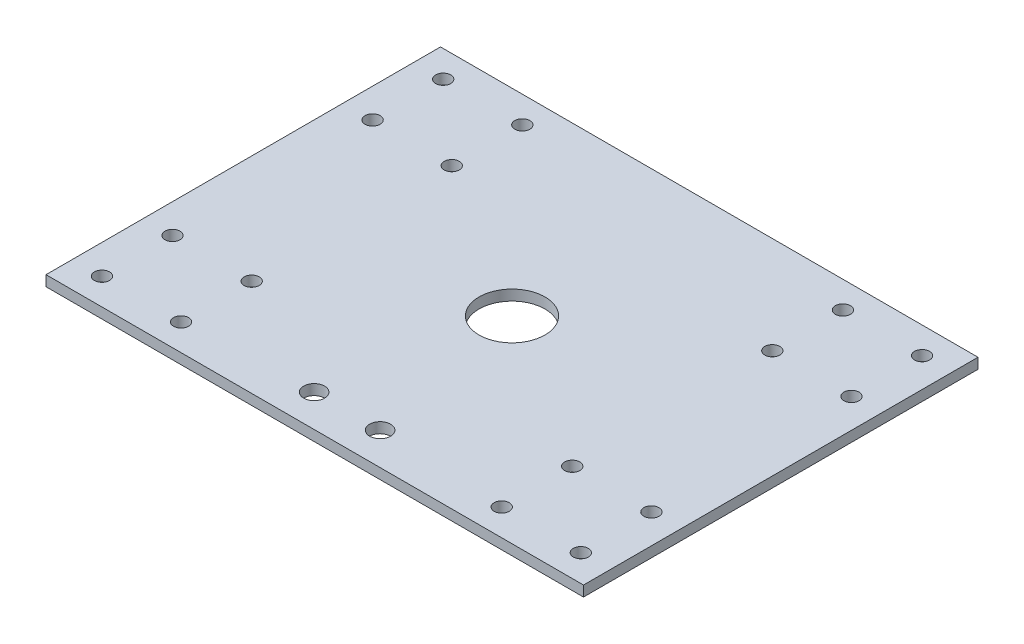
SolidWorks part; units mm, degrees
material "6061-T6 (SS)"
ref_plane "Front Plane" through (0, 0, 0) normal (0, 0, 1) x (1, 0, 0)
ref_plane "Top Plane" through (0, 0, 0) normal (0, 1, 0) x (1, 0, 0)
ref_plane "Right Plane" through (0, 0, 0) normal (1, 0, 0) x (0, 0, -1)
sketch "Sketch1" plane through (0, 0, 0) normal (0, 1, 0) x (1, 0, 0)
  line L1 (-81.5, -59.817) -> (81.5, -59.817)
  line L2 (-81.5, -59.817) -> (-81.5, 59.817)
  line L3 (-81.5, 59.817) -> (81.5, 59.817)
  line L4 (81.5, -59.817) -> (81.5, 59.817)
  line L5 (-81.5, -59.817) -> (81.5, 59.817) construction
  line L6 (-81.5, 59.817) -> (81.5, -59.817) construction
  point P0 (0, 0)
  dimension "D1" = 163
  dimension "D2" = 119.634
extrude "Boss-Extrude1" add sketch "Sketch1" along normal blind 3.175
sketch "Sketch2" plane through (0, 3.175, 0) normal (0, 1, 0) x (1, 0, 0)
  line L0 (-81.5, -59.817) -> (81.5, -59.817) construction
  line L1 (81.5, -59.817) -> (81.5, 59.817) construction
  circle A0 centre (72.61, -51.7398) radius 2.286
  circle A1 centre (48.61, -51.7398) radius 2.286
  circle A2 centre (48.61, -30.3398) radius 2.286
  circle A3 centre (72.61, -30.3398) radius 2.286
  dimension "D5" = 4.572
  dimension "D3" = 24
  dimension "D4" = 8.0772
  dimension "D6" = 21.4
  dimension "D7" = 8.89
  dimension "D1" = 2
  dimension "D2" = 2
extrude "Cut-Extrude1" cut sketch "Sketch2" against normal through all
mirror "Mirror1" about plane through (0, 0, 0) normal (0, 0, 1) of "Cut-Extrude1"
mirror "Mirror2" about plane through (0, 0, 0) normal (1, 0, 0) of "Mirror1", "Cut-Extrude1"
sketch "Sketch3" plane through (0, 3.175, 0) normal (0, 1, 0) x (1, 0, 0)
  circle A0 centre (0, 0) radius 10
  dimension "D1" = 20
extrude "Cut-Extrude2" cut sketch "Sketch3" against normal through all
sketch "Sketch4" plane through (0, 0, 0) normal (0, -1, 0) x (1, 0, 0)
  line L0 (-10, 50) -> (10, 50) construction
  point P0 (10, 50)
  point P1 (-10, 50)
  point P4 (0, 50)
  dimension "D1" = 20
  dimension "D2" = 50
hole_wizard "1/16 (0.0625) Diameter Hole1" positions "Sketch5" profile "Sketch7" hole size "1/16" standard "ANSI Inch" end condition through all
sketch "Sketch5" plane through (0, 3.175, 0) normal (0, 1, 0) x (1, 0, 0)
  point P0 (-10, -50)
  point P3 (10, -50)
sketch "Sketch7" plane through (-10, 3.175, 50) normal (1, 0, 0) x (0, 0, 1)
  line L0 (0, 0) -> (0, 3.175)
  line L1 (0, 3.175) -> (3.175, 3.175)
  line L2 (3.175, 3.175) -> (3.175, 0)
  line L5 (3.175, 0) -> (0, 0)
  line L11 (0, -6.35) -> (0, 107.95) construction
  dimension "Thru Hole Dia." = 6.35
  dimension "Thru Hole Depth" = 3.175
